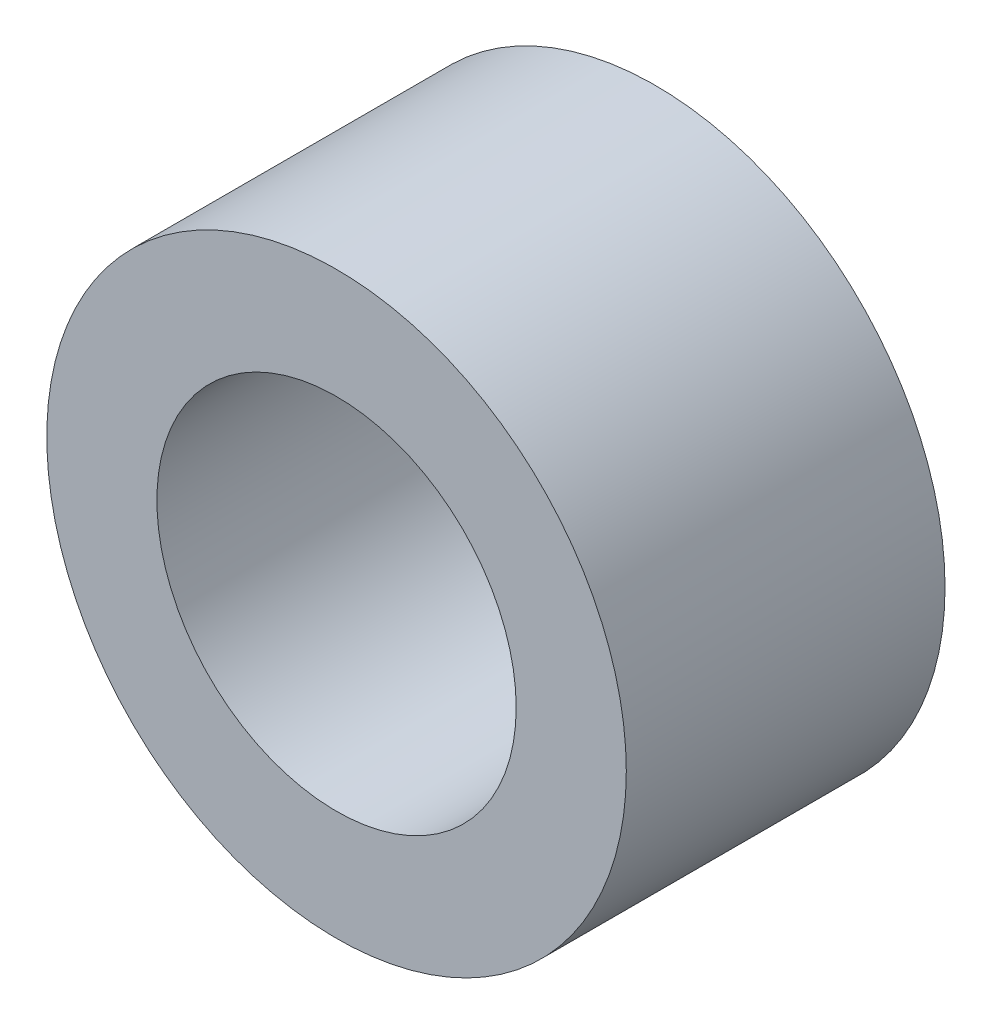
SolidWorks part; units mm, degrees
ref_plane "前视基准面" through (0, 0, 0) normal (0, 0, 1) x (1, 0, 0)
ref_plane "上视基准面" through (0, 0, 0) normal (0, 1, 0) x (1, 0, 0)
ref_plane "右视基准面" through (0, 0, 0) normal (1, 0, 0) x (0, 0, -1)
sketch "草图1" plane through (0, 0, 0) normal (0, 0, 1) x (1, 0, 0)
  circle A0 centre (0, 0) radius 5
  circle A1 centre (0, 0) radius 3.1
extrude "凸台-拉伸1" add sketch "草图1" along normal blind 5.5
